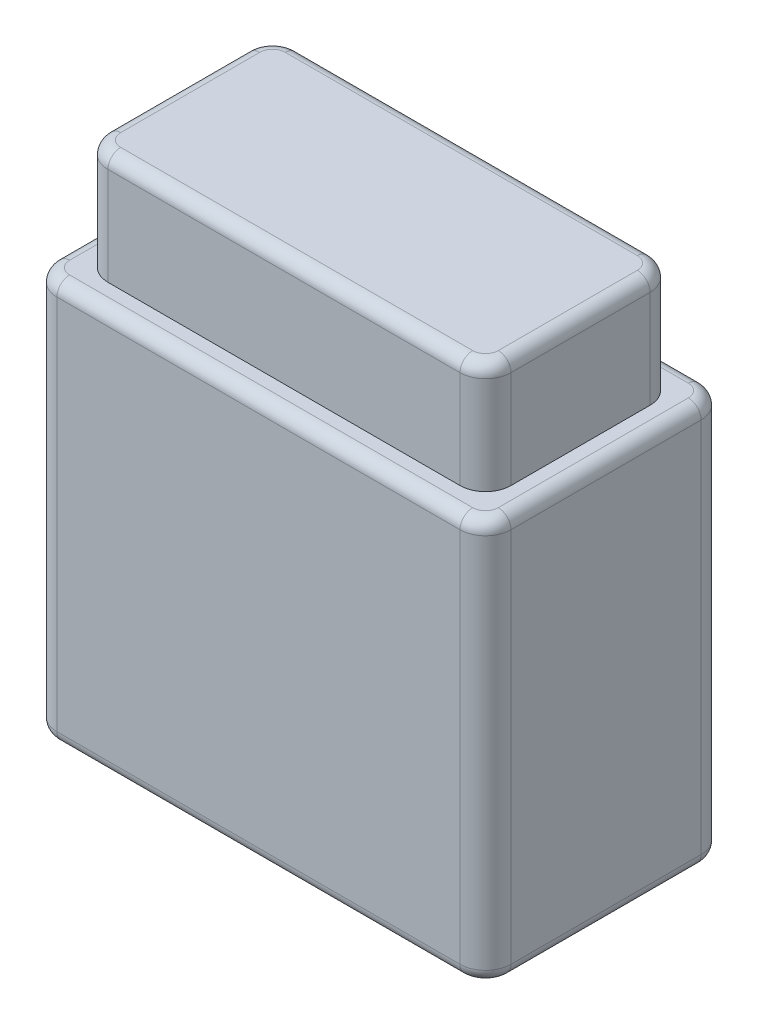
SolidWorks part; units mm, degrees
ref_plane "Front Plane" through (0, 0, 0) normal (0, 0, 1) x (1, 0, 0)
ref_plane "Top Plane" through (0, 0, 0) normal (0, 1, 0) x (1, 0, 0)
ref_plane "Right Plane" through (0, 0, 0) normal (1, 0, 0) x (0, 0, -1)
sketch "Sketch1" plane through (0, 0, 0) normal (0, 1, 0) x (1, 0, 0)
  line L1 (25.4, 0) -> (426.6, 0)
  line L2 (0, 25.4) -> (0, 214.6)
  line L3 (25.4, 240) -> (426.6, 240)
  line L4 (452, 25.4) -> (452, 214.6)
  line L5 (0, 0) -> (452, 240) construction
  line L6 (0, 240) -> (452, 0) construction
  arc A0 (0, 214.6) -> (25.4, 240) centre (25.4, 214.6) cw
  arc A1 (452, 214.6) -> (426.6, 240) centre (426.6, 214.6) ccw
  arc A2 (426.6, 0) -> (452, 25.4) centre (426.6, 25.4) ccw
  arc A3 (25.4, 0) -> (0, 25.4) centre (25.4, 25.4) cw
  point P4 (226, 120)
  dimension "D3" = 25.4
  dimension "D1" = 452
  dimension "D2" = 240
extrude "Boss-Extrude1" add sketch "Sketch1" along normal blind 400
fillet "Fillet1" radius 12.7 16 edges at (7.4395, 0, -7.4395) (7.4395, 0, -232.5605) (0, 0, -120) (444.5605, 0, -232.5605) (226, 0, -240) (444.5605, 0, -7.4395) (452, 0, -120) (226, 0, 0) (226, 400, -240) (444.5605, 400, -232.5605) (452, 400, -120) (444.5605, 400, -7.4395) (226, 400, 0) (7.4395, 400, -7.4395) (0, 400, -120) (7.4395, 400, -232.5605)
sketch "Sketch2" plane through (0, 400, 0) normal (0, 1, 0) x (1, 0, 0)
  line L0 (25.4, 12.7) -> (426.6, 12.7) construction
  line L1 (50.8, 25.4) -> (401.2, 25.4)
  line L2 (25.4, 50.8) -> (25.4, 189.2)
  line L3 (50.8, 214.6) -> (401.2, 214.6)
  line L4 (426.6, 50.8) -> (426.6, 189.2)
  line L5 (25.4, 25.4) -> (426.6, 214.6) construction
  line L6 (25.4, 214.6) -> (426.6, 25.4) construction
  line L7 (12.7, 214.6) -> (12.7, 25.4) construction
  line L8 (439.3, 25.4) -> (439.3, 214.6) construction
  line L9 (426.6, 227.3) -> (25.4, 227.3) construction
  arc A0 (426.6, 189.2) -> (401.2, 214.6) centre (401.2, 189.2) ccw
  arc A1 (25.4, 189.2) -> (50.8, 214.6) centre (50.8, 189.2) cw
  arc A2 (401.2, 25.4) -> (426.6, 50.8) centre (401.2, 50.8) ccw
  arc A3 (25.4, 50.8) -> (50.8, 25.4) centre (50.8, 50.8) ccw
  point P4 (226, 120)
  point P19 (25.4, 120)
  dimension "D1" = 25.4
  dimension "D2" = 12.7
  dimension "D3" = 12.7
  dimension "D4" = 12.7
  dimension "D5" = 12.7
extrude "Boss-Extrude3" add sketch "Sketch2" along normal blind 110
fillet "Fillet2" radius 12.7 8 edges at (426.6, 510, -120) (419.1605, 510, -32.8395) (226, 510, -25.4) (32.8395, 510, -32.8395) (25.4, 510, -120) (32.8395, 510, -207.1605) (226, 510, -214.6) (419.1605, 510, -207.1605)
